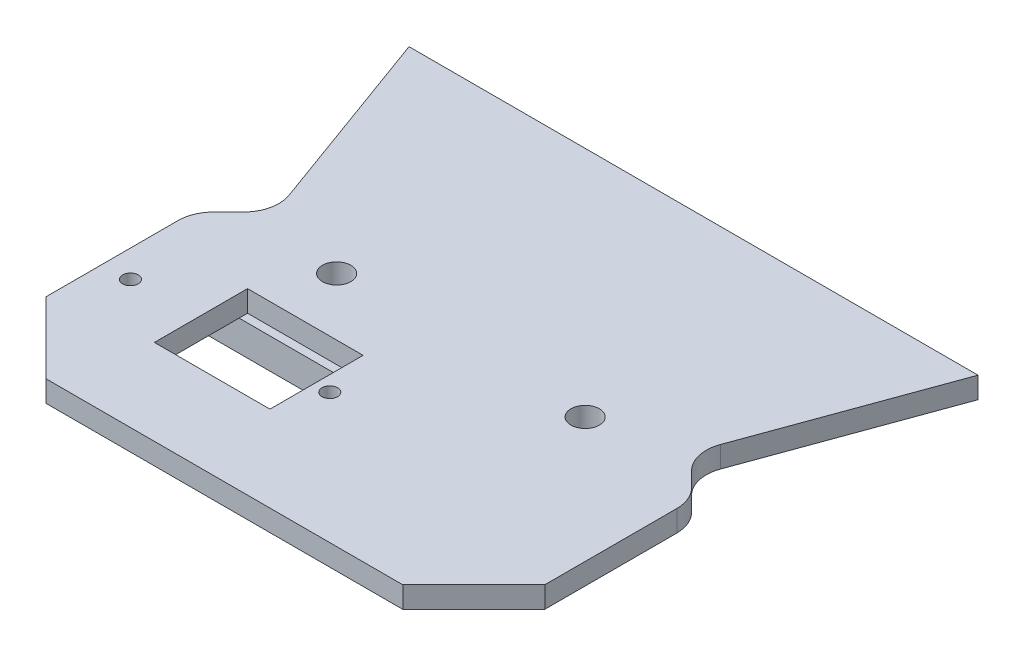
SolidWorks part; units mm, degrees
ref_plane "Front Plane" through (0, 0, 0) normal (0, 0, 1) x (1, 0, 0)
ref_plane "Top Plane" through (0, 0, 0) normal (0, 1, 0) x (1, 0, 0)
ref_plane "Right Plane" through (0, 0, 0) normal (1, 0, 0) x (0, 0, -1)
sketch "Sketch1" plane through (0, 0, 0) normal (0, 1, 0) x (1, 0, 0)
  line L0 (-17.5, 0) -> (17.5, 0) construction
  line L2 (-30.3893, 6.1749) -> (-40.0654, 32.76)
  line L3 (-40.0654, 32.76) -> (40.0654, 32.76)
  line L4 (40.0654, 32.76) -> (30.3893, 6.1749)
  line L5 (-35.1226, -23.3107) -> (-35.1226, -4.7122)
  line L6 (-35.1226, -23.3107) -> (35.1226, -23.3107)
  line L8 (-33.6581, -1.1767) -> (-31.5522, 0.9293)
  line L9 (35.1226, -23.3107) -> (35.1226, -4.7122)
  line L10 (33.6581, -1.1767) -> (31.5522, 0.9293)
  arc A2 (-31.5522, 0.9293) -> (-30.3893, 6.1749) centre (-35.0877, 4.4648) ccw
  arc A3 (-35.1226, -4.7122) -> (-33.6581, -1.1767) centre (-30.1226, -4.7122) cw
  arc A4 (35.1226, -4.7122) -> (33.6581, -1.1767) centre (30.1226, -4.7122) ccw
  arc A5 (31.5522, 0.9293) -> (30.3893, 6.1749) centre (35.0877, 4.4648) cw
  point P12 (2.2063, 0)
  dimension "D5" = 5
  dimension "D6" = 5
  dimension "D7" = 18.5985
  dimension "D8" = 30.1226
  dimension "D19" = 5
  dimension "D20" = 5
  dimension "D1" = 35
  dimension "D2" = 17.5
  dimension "D3" = 23.3107
  dimension "D4" = 18.5985
  dimension "D9" = 30.1226
  dimension "D10" = 4.7122
  dimension "D11" = 5
  dimension "D12" = 32.76
  dimension "D13" = 70
  dimension "D14" = 70
  dimension "D15" = 28.2913
  dimension "D16" = 28.2913
  dimension "D17" = 2.9782
  dimension "D18" = 2.9782
extrude "Boss-Extrude1" add sketch "Sketch1" along normal blind 3
sketch "Sketch2" plane through (0, 3, 0) normal (0, 1, 0) x (1, 0, 0)
  circle A1 centre (17.5, 0) radius 2
  circle A2 centre (-17.5, 0) radius 2
  dimension "D1" = 4
  dimension "D2" = 4
  dimension "D3" = 35
extrude "Boss-Extrude2" add sketch "Sketch2" along normal blind 10
sketch "Sketch3" plane through (0, 3, 0) normal (0, 1, 0) x (1, 0, 0)
  circle A0 centre (-31.3008, -15.2415) radius 1.1 construction
  circle A1 centre (-31.3008, -15.2415) radius 1.1
  circle A2 centre (-3.5021, -14.9671) radius 1.1 construction
  circle A3 centre (-3.5021, -14.9671) radius 1.1
  dimension "D1" = 15.2415
  dimension "D2" = 27.7986
  dimension "D3" = 3.5021
extrude "Cut-Extrude1" cut sketch "Sketch3" against normal blind 10
sketch "Sketch4" plane through (0, 0, 0) normal (0, -1, 0) x (1, 0, 0)
  line L0 (-3.5021, 14.9671) -> (-31.3008, 15.2415) construction
  line L1 (-28.6015, 9.3149) -> (-6.2015, 9.3149)
  line L2 (-28.6015, 9.3149) -> (-28.6015, 21.1149)
  line L3 (-28.6015, 21.1149) -> (-6.2015, 21.1149)
  line L4 (-6.2015, 9.3149) -> (-6.2015, 21.1149)
  line L5 (-30.6015, 7.3149) -> (-30.6015, 23.1149)
  line L6 (-30.6015, 23.1149) -> (-4.2015, 23.1149)
  line L7 (-4.2015, 7.3149) -> (-4.2015, 23.1149)
  line L8 (-30.6015, 7.3149) -> (-4.2015, 7.3149)
  circle A0 centre (-3.5021, 14.9671) radius 1.1 construction
  circle A1 centre (-3.5021, 14.9671) radius 1.1 construction
  circle A2 centre (-31.3008, 15.2415) radius 1.1 construction
  circle A3 centre (-31.3008, 15.2415) radius 1.1 construction
  point P10 (-17.4015, 15.1043)
  point P11 (-17.4015, 9.3149)
  point P12 (-28.6015, 15.2149)
  dimension "D1" = 22.4
  dimension "D2" = 11.8
  dimension "D3" = 2
extrude "Boss-Extrude3" add sketch "Sketch4" along normal blind 4.3
sketch "Sketch5" plane through (0, 0, 0) normal (0, -1, 0) x (1, 0, 0)
  line L0 (-30.6015, 23.1149) -> (-30.6015, 7.3149)
  line L1 (-30.6015, 7.3149) -> (-33.6015, 9.0469)
  line L2 (-33.6015, 9.0469) -> (-33.6015, 21.3828)
  line L3 (-33.6015, 21.3828) -> (-30.6015, 23.1149)
  line L4 (-17.4015, 7.3149) -> (-17.4015, 15.1715) construction
  line L5 (-30.6015, 7.3149) -> (-4.2015, 7.3149) construction
  line L6 (-1.2015, 21.3828) -> (-4.2015, 23.1149)
  line L7 (-1.2015, 9.0469) -> (-1.2015, 21.3828)
  line L8 (-4.2015, 7.3149) -> (-1.2015, 9.0469)
  line L9 (-4.2015, 23.1149) -> (-4.2015, 7.3149)
  dimension "D1" = 3
  dimension "D2" = 60
  dimension "D3" = 60
extrude "Boss-Extrude4" add sketch "Sketch5" along normal blind 4.3
sketch "Sketch6" plane through (0, 3, 0) normal (0, 1, 0) x (1, 0, 0)
  circle A1 centre (-31.3008, -15.2415) radius 1.1
  circle A2 centre (-31.3008, -15.2415) radius 1.1
  circle A3 centre (-3.5021, -14.9671) radius 1.1
  circle A4 centre (-3.5021, -14.9671) radius 1.1
  dimension "D1" = 0
  dimension "D2" = 0
extrude "Cut-Extrude2" cut sketch "Sketch6" against normal blind 20.3
sketch "Sketch7" plane through (0, 0, 0) normal (0, -1, 0) x (1, 0, 0)
  line L1 (-5.6477, 21.2432) -> (-21.9244, 21.2432)
  line L2 (-5.6477, 21.2432) -> (-5.6477, 8.122)
  line L3 (-5.6477, 8.122) -> (-21.9244, 8.122)
  line L4 (-21.9244, 21.2432) -> (-21.9244, 8.122)
extrude "Cut-Extrude3" cut sketch "Sketch7" against normal blind 20.3
sketch "Sketch8" plane through (0, 3, 0) normal (0, 1, 0) x (1, 0, 0)
  line L0 (-35.1226, -23.3107) -> (35.1226, -23.3107) construction
  line L1 (-35.1226, -23.3107) -> (35.1226, -23.3107)
  line L2 (-35.1226, -23.3107) -> (-25.1226, -33.3107)
  line L3 (-25.1226, -33.3107) -> (25.1226, -33.3107)
  line L4 (25.1226, -33.3107) -> (35.1226, -23.3107)
  dimension "D1" = 10
  dimension "D2" = 45
  dimension "D3" = 45
extrude "Boss-Extrude5" add sketch "Sketch8" against normal blind 3
sketch "Sketch10" plane through (0, 13, 0) normal (0, 1, 0) x (1, 0, 0)
  circle A1 centre (-17.5, 0) radius 2
  circle A2 centre (-17.5, 0) radius 2
  circle A3 centre (17.5, 0) radius 2
  circle A4 centre (17.5, 0) radius 2
  dimension "D1" = 0
  dimension "D2" = 0
extrude "Cut-Extrude4" cut sketch "Sketch10" against normal blind 21
